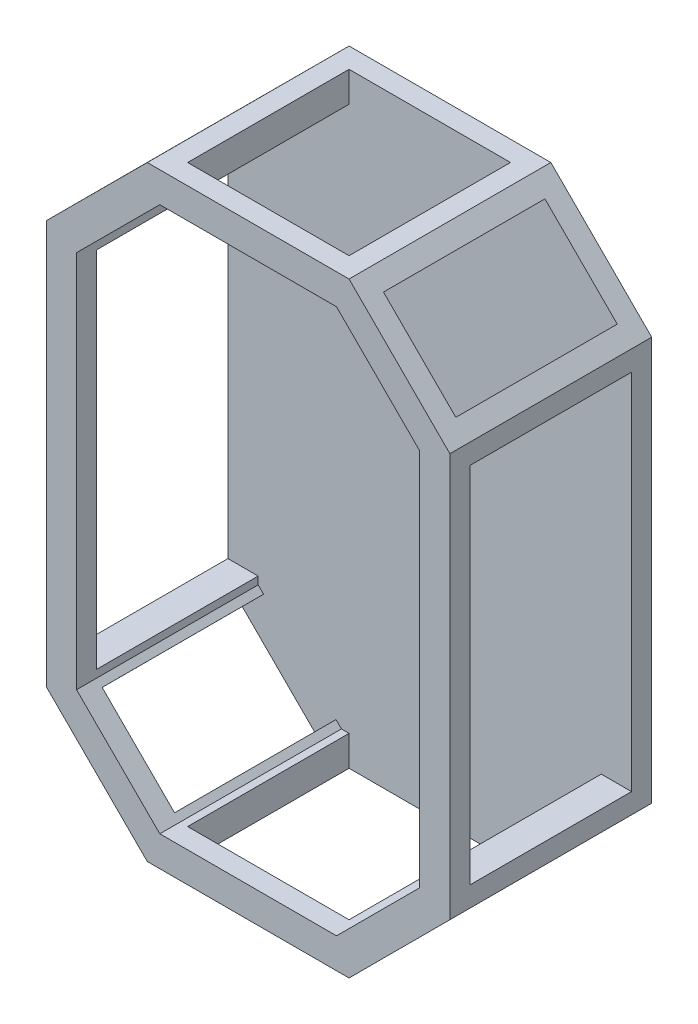
SolidWorks part; units mm, degrees
ref_plane "Front Plane" through (0, 0, 0) normal (1, 0, 0) x (0, 1, 0)
ref_plane "Top Plane" through (0, 0, 0) normal (0, 0, 1) x (0, 1, 0)
ref_plane "Right Plane" through (0, 0, 0) normal (0, 1, 0) x (-1, 0, 0)
sketch "Sketch1" plane through (0, 0, 0) normal (0, 0, 1) x (0, 1, 0)
  line L0 (-400, 0) -> (-499.9648, 99.9648)
  line L1 (0, 0) -> (-400, 0)
  line L2 (0, 0) -> (0, 400)
  line L3 (0, 400) -> (-400, 400)
  line L4 (-400, 0) -> (-400, 400)
  line L5 (-499.9648, 99.9648) -> (-499.9648, 299.9149)
  line L6 (-499.9648, 299.9149) -> (-400, 400)
  line L7 (0, 0) -> (99.9648, 99.9648)
  line L8 (99.9648, 99.9648) -> (99.9648, 299.9149)
  line L9 (99.9648, 299.9149) -> (0, 400)
  point P5 (0, 0)
  point P10 (0, 0)
  dimension "D1" = 400
  dimension "D2" = 400
extrude "Boss-Extrude1" add sketch "Sketch1" along normal blind 200 contours L0 L5 L6 L3 L9 L8 L7 L1
sketch "Sketch4" plane through (0, 0, 200) normal (0, 0, 1) x (1, 0, 0)
  line L16 (-30, -387.5736) -> (-30, -12.4264)
  line L17 (-30, -12.4264) -> (-112.3912, 69.9648)
  line L18 (-112.3912, 69.9648) -> (-287.499, 69.9648)
  line L19 (-287.499, 69.9648) -> (-370, -12.437)
  line L20 (-370, -12.437) -> (-370, -387.563)
  line L21 (-370, -387.563) -> (-287.499, -469.9648)
  line L22 (-287.499, -469.9648) -> (-112.3912, -469.9648)
  line L23 (-112.3912, -469.9648) -> (-30, -387.5736)
  line L24 (-30, -387.5736) -> (-30, -12.4264)
  line L25 (-30, -12.4264) -> (-112.3912, 69.9648)
  line L26 (-112.3912, 69.9648) -> (-287.499, 69.9648)
  line L27 (-287.499, 69.9648) -> (-370, -12.437)
  line L28 (-370, -12.437) -> (-370, -387.563)
  line L29 (-370, -387.563) -> (-287.499, -469.9648)
  line L30 (-287.499, -469.9648) -> (-112.3912, -469.9648)
  line L31 (-112.3912, -469.9648) -> (-30, -387.5736)
  dimension "D1" = 30
extrude "Cut-Extrude1" cut sketch "Sketch4" against normal blind 180
sketch "Sketch6" plane through (-400, 0, 0) normal (-1, 0, 0) x (0, -1, 0)
  line L8 (20, 20) -> (380, 20)
  line L9 (380, 20) -> (380, 180)
  line L10 (380, 180) -> (20, 180)
  line L11 (20, 180) -> (20, 20)
  line L12 (20, 20) -> (380, 20)
  line L13 (380, 20) -> (380, 180)
  line L14 (380, 180) -> (20, 180)
  line L15 (20, 180) -> (20, 20)
  dimension "D1" = 20
extrude "Cut-Extrude2" cut sketch "Sketch6" against normal through all
sketch "Sketch7" plane through (-199.7593, 199.9999, 0) normal (-0.7067, 0.7075, 0) x (-0.7075, -0.7067, 0)
  line L8 (161.5562, 20) -> (263.0128, 20)
  line L9 (263.0128, 20) -> (263.0128, 180)
  line L10 (263.0128, 180) -> (161.5562, 180)
  line L11 (161.5562, 180) -> (161.5562, 20)
  line L12 (161.5562, 20) -> (263.0128, 20)
  line L13 (263.0128, 20) -> (263.0128, 180)
  line L14 (263.0128, 180) -> (161.5562, 180)
  line L15 (161.5562, 180) -> (161.5562, 20)
  dimension "D1" = 20
extrude "Cut-Extrude3" cut sketch "Sketch7" against normal blind 30
sketch "Sketch8" plane through (-399.7592, -400.2405, 0) normal (-0.7067, -0.7075, 0) x (0.7075, -0.7067, 0)
  line L8 (19.6596, 20) -> (121.1163, 20)
  line L9 (121.1163, 20) -> (121.1163, 180)
  line L10 (121.1163, 180) -> (19.6596, 180)
  line L11 (19.6596, 180) -> (19.6596, 20)
  line L12 (19.6596, 20) -> (121.1163, 20)
  line L13 (121.1163, 20) -> (121.1163, 180)
  line L14 (121.1163, 180) -> (19.6596, 180)
  line L15 (19.6596, 180) -> (19.6596, 20)
  dimension "D1" = 20
extrude "Cut-Extrude4" cut sketch "Sketch8" against normal blind 30
sketch "Sketch9" plane through (0, 0, 0) normal (0.7071, 0.7071, 0) x (-0.7071, 0.7071, 0)
  line L8 (20, 20) -> (121.3715, 20)
  line L9 (121.3715, 20) -> (121.3715, 180)
  line L10 (121.3715, 180) -> (20, 180)
  line L11 (20, 180) -> (20, 20)
  line L12 (20, 20) -> (121.3715, 20)
  line L13 (121.3715, 20) -> (121.3715, 180)
  line L14 (121.3715, 180) -> (20, 180)
  line L15 (20, 180) -> (20, 20)
  dimension "D1" = 20
extrude "Cut-Extrude5" cut sketch "Sketch9" against normal blind 30
sketch "Sketch10" plane through (200, -200, 0) normal (0.7071, -0.7071, 0) x (0.7071, 0.7071, 0)
  line L8 (-404.2142, 20) -> (-302.8427, 20)
  line L9 (-302.8427, 20) -> (-302.8427, 180)
  line L10 (-302.8427, 180) -> (-404.2142, 180)
  line L11 (-404.2142, 180) -> (-404.2142, 20)
  line L12 (-404.2142, 20) -> (-302.8427, 20)
  line L13 (-302.8427, 20) -> (-302.8427, 180)
  line L14 (-302.8427, 180) -> (-404.2142, 180)
  line L15 (-404.2142, 180) -> (-404.2142, 20)
  dimension "D1" = 20
extrude "Cut-Extrude6" cut sketch "Sketch10" against normal blind 30
sketch "Sketch11" plane through (0, -499.9648, 0) normal (0, -1, 0) x (1, 0, 0)
  line L8 (-279.9149, 20) -> (-119.9648, 20)
  line L9 (-119.9648, 20) -> (-119.9648, 180)
  line L10 (-119.9648, 180) -> (-279.9149, 180)
  line L11 (-279.9149, 180) -> (-279.9149, 20)
  line L12 (-279.9149, 20) -> (-119.9648, 20)
  line L13 (-119.9648, 20) -> (-119.9648, 180)
  line L14 (-119.9648, 180) -> (-279.9149, 180)
  line L15 (-279.9149, 180) -> (-279.9149, 20)
  dimension "D1" = 20
extrude "Cut-Extrude7" cut sketch "Sketch11" against normal through all
